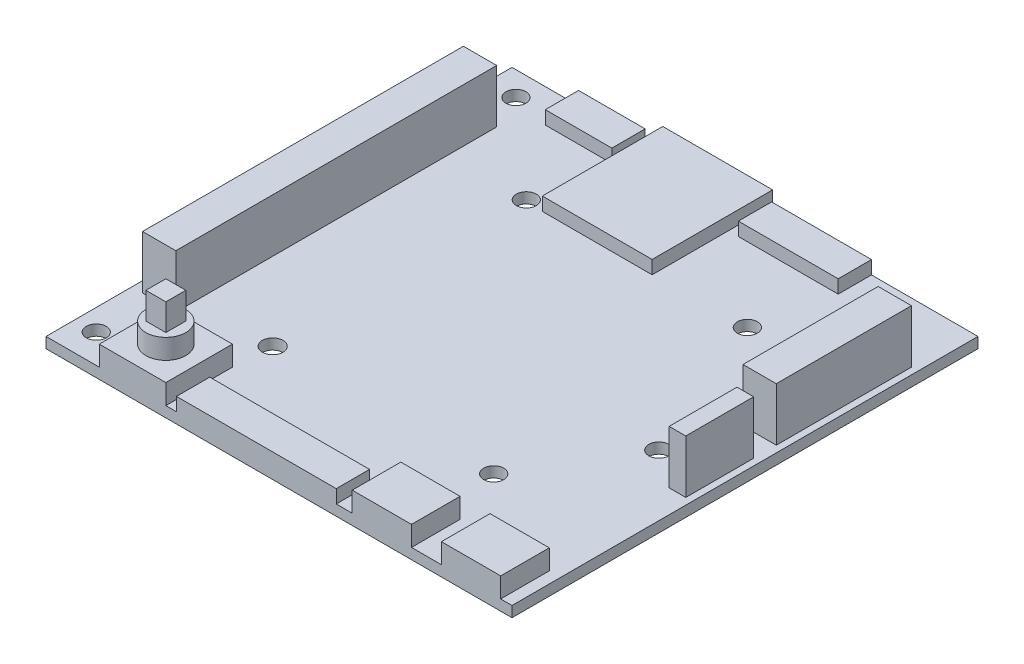
SolidWorks part; units mm, degrees
ref_plane "前视基准面" through (0, 0, 0) normal (0, 0, 1) x (1, 0, 0)
ref_plane "上视基准面" through (0, 0, 0) normal (0, 1, 0) x (1, 0, 0)
ref_plane "右视基准面" through (0, 0, 0) normal (1, 0, 0) x (0, 0, -1)
sketch "草图1" plane through (0, 0, 0) normal (0, 1, 0) x (1, 0, 0)
  line L0 (0, 0) -> (32.6781, 0) construction
  line L1 (-18.31, -15.74) -> (51.69, -15.74)
  line L2 (-18.31, -15.74) -> (-18.31, 54.26)
  line L3 (-18.31, 54.26) -> (51.69, 54.26)
  line L4 (51.69, -15.74) -> (51.69, 54.26)
  line L5 (0, 0) -> (0, 38.1) construction
  line L6 (0, 38.1) -> (33.2, 38.1) construction
  line L7 (33.2, 38.1) -> (33.2, 0) construction
  circle A0 centre (0, 0) radius 1.55
  circle A1 centre (33.2, 0) radius 1.5
  circle A2 centre (0, 38.1) radius 1.5
  circle A3 centre (33.2, 38.1) radius 1.5
  circle A4 centre (-14.1, 50.64) radius 1.5
  circle A5 centre (41.9, 49.7) radius 1.5
  circle A6 centre (42.5, 15.5) radius 1.5
  circle A7 centre (-15.1, -11.4) radius 1.5
  dimension "D5" = 3.1
  dimension "D8" = 3
  dimension "D9" = 3
  dimension "D10" = 3
  dimension "D19" = 3
  dimension "D20" = 3
  dimension "D21" = 3
  dimension "D22" = 3
  dimension "D1" = 70
  dimension "D2" = 70
  dimension "D3" = 18.31
  dimension "D4" = 15.74
  dimension "D6" = 33.2
  dimension "D7" = 38.1
  dimension "D11" = 14.1
  dimension "D12" = 50.64
  dimension "D13" = 15.1
  dimension "D14" = 11.4
  dimension "D15" = 42.5
  dimension "D16" = 15.5
  dimension "D17" = 41.9
  dimension "D18" = 49.7
extrude "凸台-拉伸1" add sketch "草图1" along normal blind 1.6
sketch "草图3" plane through (0, 1.6, 0) normal (0, 1, 0) x (1, 0, 0)
  line L1 (2.7, 37.8) -> (19.2, 37.8)
  line L2 (2.7, 37.8) -> (2.7, 55.9)
  line L3 (2.7, 55.9) -> (19.2, 55.9)
  line L4 (19.2, 37.8) -> (19.2, 55.9)
  dimension "D1" = 2.7
  dimension "D2" = 37.8
  dimension "D3" = 16.5
  dimension "D4" = 18.1
extrude "凸台-拉伸2" add sketch "草图3" along normal blind 2
sketch "草图5" plane through (0, 1.6, 0) normal (0, 1, 0) x (1, 0, 0)
  line L0 (-18.31, -15.74) -> (51.69, -15.74) construction
  line L1 (49.99, -15.74) -> (41.09, -15.74)
  line L2 (49.99, -15.74) -> (49.99, -8.44)
  line L3 (49.99, -8.44) -> (41.09, -8.44)
  line L4 (41.09, -15.74) -> (41.09, -8.44)
  line L5 (51.69, -15.74) -> (51.69, 54.26) construction
  line L6 (36.59, -15.74) -> (27.69, -15.74)
  line L7 (36.59, -15.74) -> (36.59, -8.44)
  line L8 (36.59, -8.44) -> (27.69, -8.44)
  line L9 (27.69, -15.74) -> (27.69, -8.44)
  dimension "D1" = 1.7
  dimension "D2" = 8.9
  dimension "D3" = 7.3
  dimension "D4" = 8.9
  dimension "D5" = 7.3
  dimension "D6" = 4.5
extrude "凸台-拉伸3" add sketch "草图5" along normal blind 3
sketch "草图6" plane through (0, 1.6, 0) normal (0, 1, 0) x (1, 0, 0)
  line L0 (-18.31, -15.74) -> (27.69, -15.74) construction
  line L1 (-10.31, -15.74) -> (-0.31, -15.74)
  line L2 (-10.31, -15.74) -> (-10.31, -5.74)
  line L3 (-10.31, -5.74) -> (-0.31, -5.74)
  line L4 (-0.31, -15.74) -> (-0.31, -5.74)
  line L5 (-18.31, 54.26) -> (-18.31, -15.74) construction
  dimension "D1" = 10
  dimension "D2" = 10
  dimension "D3" = 8
extrude "凸台-拉伸4" add sketch "草图6" along normal blind 3
sketch "草图7" plane through (0, 4.6, 0) normal (0, 1, 0) x (1, 0, 0)
  line L0 (-10.31, -5.74) -> (-0.31, -15.74) construction
  line L1 (-0.31, -5.74) -> (-10.31, -15.74) construction
  circle A0 centre (-5.31, -10.74) radius 3
  dimension "D1" = 6
extrude "凸台-拉伸5" add sketch "草图7" along normal blind 3
sketch "草图8" plane through (0, 7.6, 0) normal (0, 1, 0) x (1, 0, 0)
  line L1 (-6.81, -9.24) -> (-3.81, -9.24)
  line L2 (-6.81, -9.24) -> (-6.81, -12.24)
  line L3 (-6.81, -12.24) -> (-3.81, -12.24)
  line L4 (-3.81, -9.24) -> (-3.81, -12.24)
  line L5 (-6.81, -9.24) -> (-3.81, -12.24) construction
  line L6 (-6.81, -12.24) -> (-3.81, -9.24) construction
  point P0 (-5.31, -10.74)
  dimension "D1" = 3
  dimension "D2" = 3
extrude "凸台-拉伸6" add sketch "草图8" along normal blind 4
sketch "草图9" plane through (0, 1.6, 0) normal (0, 1, 0) x (1, 0, 0)
  line L0 (-0.31, -15.74) -> (27.69, -15.74) construction
  line L1 (1.29, -15.74) -> (25.29, -15.74)
  line L2 (1.29, -15.74) -> (1.29, -10.74)
  line L3 (1.29, -10.74) -> (25.29, -10.74)
  line L4 (25.29, -15.74) -> (25.29, -10.74)
  line L5 (2.7, 54.26) -> (-18.31, 54.26) construction
  line L6 (-8.31, 54.26) -> (1.69, 54.26)
  line L7 (-8.31, 54.26) -> (-8.31, 49.26)
  line L8 (-8.31, 49.26) -> (1.69, 49.26)
  line L9 (1.69, 54.26) -> (1.69, 49.26)
  line L10 (51.69, 54.26) -> (19.2, 54.26) construction
  line L11 (20.69, 54.26) -> (35.69, 54.26)
  line L12 (20.69, 54.26) -> (20.69, 49.26)
  line L13 (20.69, 49.26) -> (35.69, 49.26)
  line L14 (35.69, 54.26) -> (35.69, 49.26)
  line L15 (-18.31, 54.26) -> (-18.31, -15.74) construction
  line L16 (51.69, -15.74) -> (51.69, 54.26) construction
  dimension "D1" = 19.6
  dimension "D2" = 24
  dimension "D3" = 5
  dimension "D4" = 10
  dimension "D5" = 10
  dimension "D6" = 16
  dimension "D7" = 15
  dimension "D8" = 5
  dimension "D9" = 5
extrude "凸台-拉伸7" add sketch "草图9" along normal blind 2
sketch "草图10" plane through (0, 1.6, 0) normal (0, 1, 0) x (1, 0, 0)
  line L0 (-18.31, 54.26) -> (-18.31, -15.74) construction
  line L1 (-16.71, -2.84) -> (-11.71, -2.84)
  line L2 (-16.71, -2.84) -> (-16.71, 45.36)
  line L3 (-16.71, 45.36) -> (-11.71, 45.36)
  line L4 (-11.71, -2.84) -> (-11.71, 45.36)
  line L5 (45.69, 45.26) -> (50.69, 45.26)
  line L6 (45.69, 45.26) -> (45.69, 24.96)
  line L7 (45.69, 24.96) -> (50.69, 24.96)
  line L8 (50.69, 45.26) -> (50.69, 24.96)
  line L9 (50.69, 21.56) -> (48.19, 21.56)
  line L10 (50.69, 21.56) -> (50.69, 11.36)
  line L11 (50.69, 11.36) -> (48.19, 11.36)
  line L12 (48.19, 21.56) -> (48.19, 11.36)
  line L13 (-18.31, -15.74) -> (-10.31, -15.74) construction
  line L14 (51.69, -15.74) -> (51.69, 54.26) construction
  line L15 (51.69, 54.26) -> (35.69, 54.26) construction
  line L16 (41.09, -15.74) -> (49.99, -15.74) construction
  dimension "D1" = 1.6
  dimension "D2" = 12.9
  dimension "D3" = 5
  dimension "D4" = 48.2
  dimension "D5" = 1
  dimension "D6" = 9
  dimension "D7" = 5
  dimension "D8" = 20.3
  dimension "D9" = 27.1
  dimension "D10" = 1
  dimension "D11" = 2.5
  dimension "D12" = 10.2
extrude "凸台-拉伸8" add sketch "草图10" along normal blind 8
